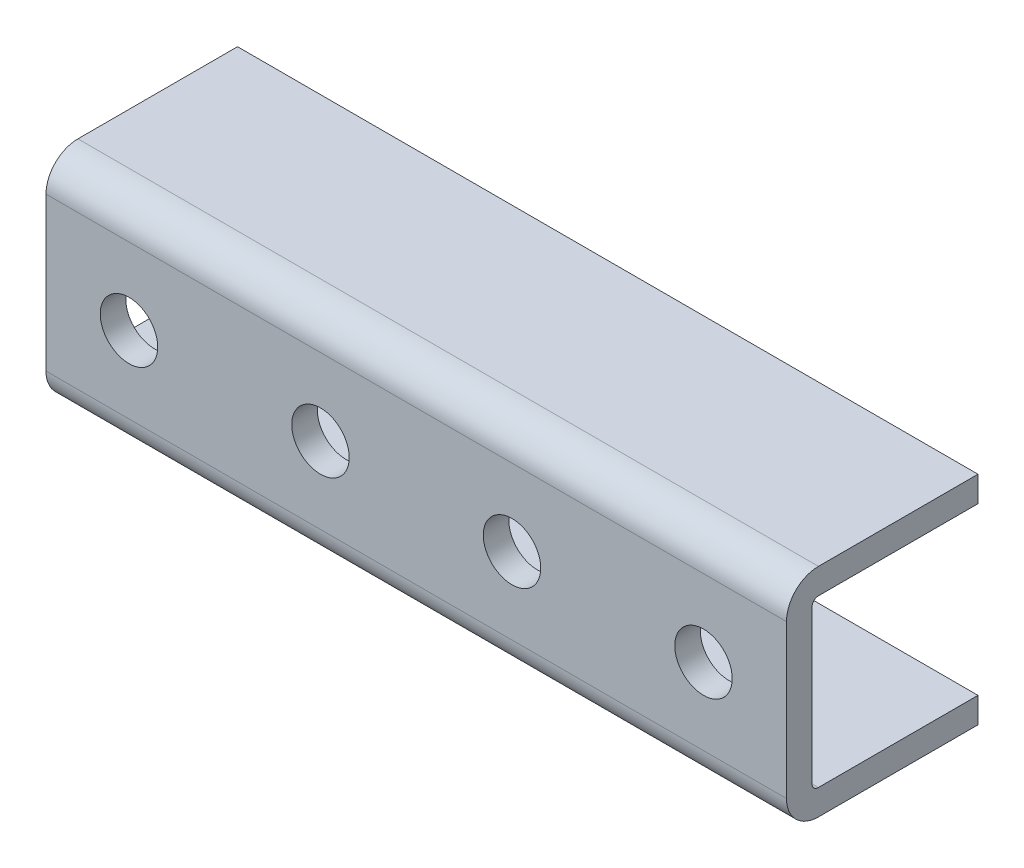
SolidWorks part; units mm, degrees
ref_plane "Front Plane" through (0, 0, 0) normal (0, 0, 1) x (1, 0, 0)
ref_plane "Top Plane" through (0, 0, 0) normal (0, 1, 0) x (1, 0, 0)
ref_plane "Right Plane" through (0, 0, 0) normal (1, 0, 0) x (0, 0, -1)
sketch "Sketch1" plane through (0, 0, 0) normal (0, 0, 1) x (1, 0, 0)
  line L0 (-92.075, 0) -> (92.075, 0) construction
  line L1 (-92.075, 26.9875) -> (92.075, 26.9875)
  line L2 (-92.075, 26.9875) -> (-92.075, -26.9875)
  line L3 (-92.075, -26.9875) -> (92.075, -26.9875)
  line L4 (92.075, 26.9875) -> (92.075, -26.9875)
  line L5 (0, 20.6375) -> (0, -20.6375) construction
  dimension "D1" = 53.975
  dimension "A" = 184.15
  dimension "B" = 41.275
extrude "Boss-Extrude1" add sketch "Sketch1" along normal mid plane 47.625
fillet "Fillet1" radius 7.9375 2 edges at (0, -26.9875, 23.8125) (0, 26.9875, 23.8125)
shell "Shell1" thickness 6.35
sketch "Sketch2" plane through (0, 0, 23.8125) normal (0, 0, 1) x (1, 0, 0)
  line L0 (-92.075, 0) -> (92.075, 0) construction
  line L1 (-92.075, 19.05) -> (-92.075, -19.05) construction
  line L2 (92.075, -19.05) -> (92.075, 19.05) construction
  circle A0 centre (-71.4375, 0) radius 7.1438
  circle A1 centre (-23.8125, 0) radius 7.1438
  circle A2 centre (23.8125, 0) radius 7.1438
  circle A3 centre (71.4375, 0) radius 7.1438
  dimension "Hole Size" = 14.2875
  dimension "Spacing" = 47.625
  dimension "D3" = 47.625
  dimension "D4" = 47.625
  dimension "D5" = 23.8125
extrude "Cut-Extrude1" cut sketch "Sketch2" against normal blind 47.625
equation "\"D1@Sketch1\" = (\"Thickness@Shell1\"*2)+1.625"
equation "\"D1@Boss-Extrude1\" = \"B@Sketch1\"+\"Thickness@Shell1\""
equation "\"D4@Sketch2\" = \"Spacing@Sketch2\""
equation "\"D3@Sketch2\" = \"Spacing@Sketch2\""
equation "\"D5@Sketch2\" = \"Spacing@Sketch2\"/2"
